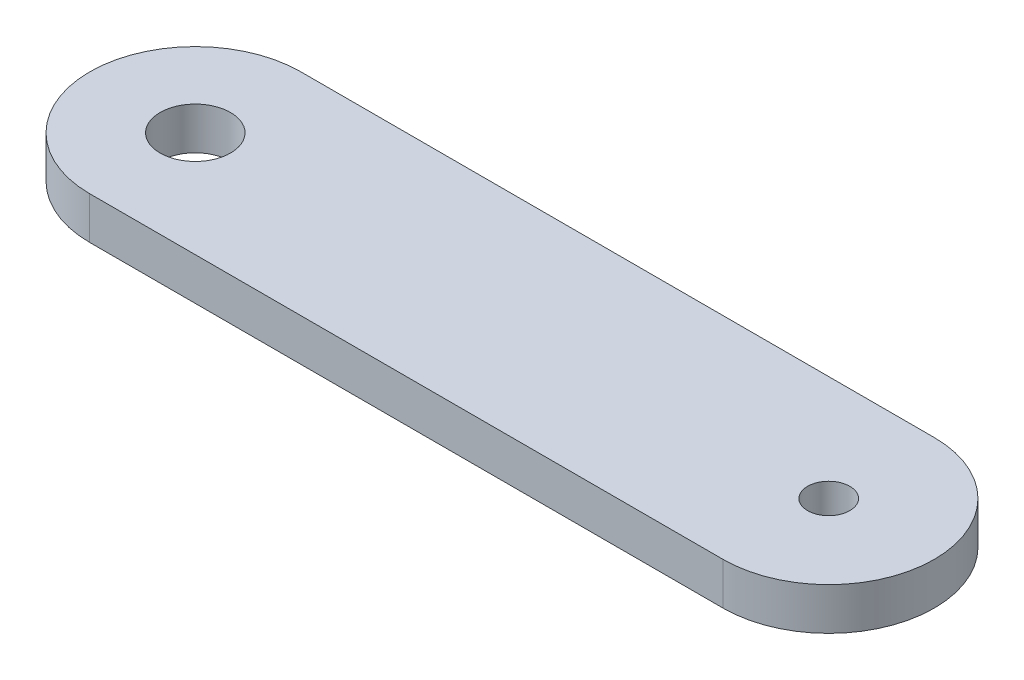
SolidWorks part; units mm, degrees
ref_plane "Front Plane" through (0, 0, 0) normal (0, 0, 1) x (1, 0, 0)
ref_plane "Top Plane" through (0, 0, 0) normal (0, 1, 0) x (1, 0, 0)
ref_plane "Right Plane" through (0, 0, 0) normal (1, 0, 0) x (0, 0, -1)
sketch "Sketch2" plane through (0, 0, 0) normal (0, 1, 0) x (1, 0, 0)
  line L1 (-45, 15) -> (45, 15)
  line L3 (-45, -15) -> (45, -15)
  arc A0 (-45, 15) -> (-45, -15) centre (-45, 0) ccw
  arc A1 (45, -15) -> (45, 15) centre (45, 0) ccw
  circle A2 centre (-45, 0) radius 5
  circle A3 centre (45, 0) radius 3
  point P0 (0, 0)
extrude "Boss-Extrude1" add sketch "Sketch2" along normal blind 6
